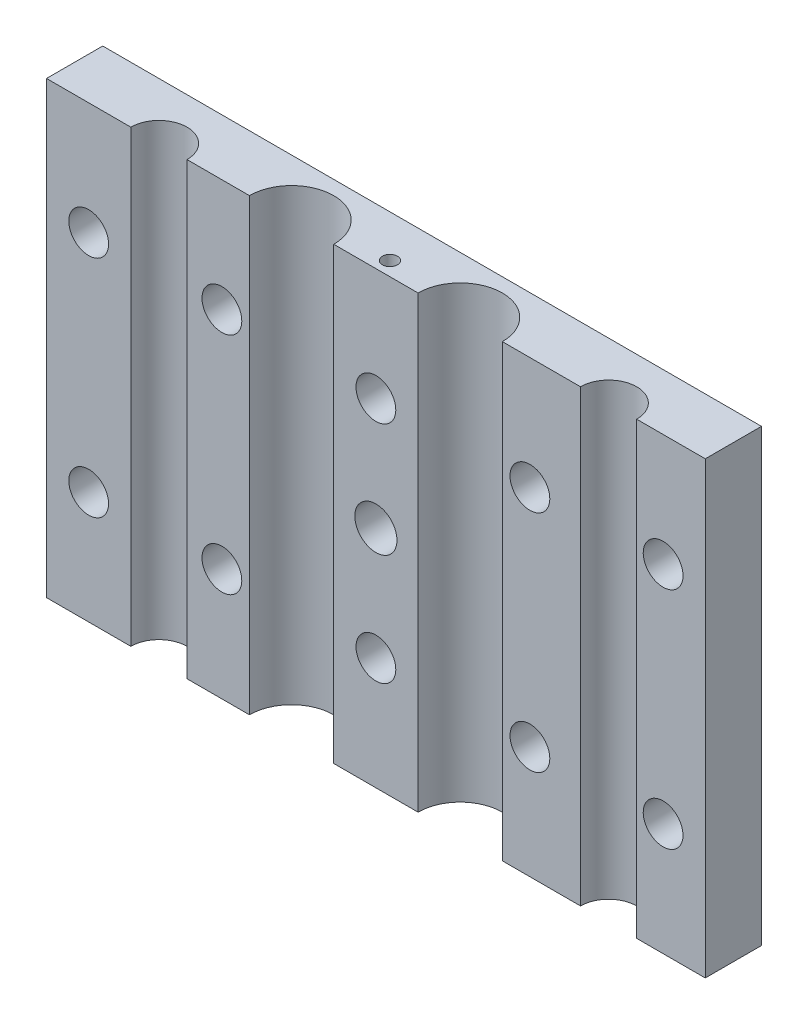
SolidWorks part; units mm, degrees
material "Copper"
ref_plane "Front Plane" through (0, 0, 0) normal (0, 0, 1) x (1, 0, 0)
ref_plane "Top Plane" through (0, 0, 0) normal (0, 1, 0) x (1, 0, 0)
ref_plane "Right Plane" through (0, 0, 0) normal (1, 0, 0) x (0, 0, -1)
sketch "Sketch1" plane through (0, 0, 0) normal (0, 1, 0) x (1, 0, 0)
  line L1 (-37.211, 25.4) -> (37.211, 25.4)
  line L2 (-37.211, 25.4) -> (-37.211, -25.4)
  line L3 (-37.211, -25.4) -> (37.211, -25.4)
  line L4 (37.211, 25.4) -> (37.211, -25.4)
  dimension "D1" = 50.8
  dimension "D2" = 74.422
  dimension "D3" = 37.211
  dimension "D4" = 25.4
extrude "Boss-Extrude1" add sketch "Sketch1" along normal blind 6.35
sketch "Sketch2" plane through (0, 0, 25.4) normal (0, 0, 1) x (1, 0, 0)
  line L0 (-37.211, 0) -> (37.211, 0) construction
  line L1 (-37.211, 6.35) -> (-37.211, 0) construction
  circle A0 centre (-24.511, 0) radius 3.175
  circle A1 centre (26.289, 0) radius 3.175
  dimension "D3" = 6.35
  dimension "D1" = 50.8
  dimension "D2" = 12.7
extrude "Cut-Extrude1" cut sketch "Sketch2" against normal through all
sketch "Sketch3" plane through (0, 0, 25.4) normal (0, 0, 1) x (1, 0, 0)
  line L0 (-21.336, 0) -> (23.114, 0) construction
  circle A0 centre (-9.525, 0) radius 4.7625
  circle A1 centre (9.525, 0) radius 4.7625
  dimension "D1" = 9.525
  dimension "D2" = 19.05
  dimension "D3" = 9.525
extrude "Cut-Extrude2" cut sketch "Sketch3" against normal through all
hole_wizard "#8 Clearance Hole1" positions "Sketch5" profile "Sketch4" hole size "#8" standard "ANSI Inch" end condition through all
sketch "Sketch5" plane through (0, 6.35, 0) normal (0, 1, 0) x (1, 0, 0)
  line L2 (37.211, 25.4) -> (-37.211, 25.4) construction
  line L3 (-37.211, -25.4) -> (37.211, -25.4) construction
  line L4 (-37.211, 25.4) -> (-37.211, -25.4) construction
  line L5 (37.211, -25.4) -> (37.211, 25.4) construction
  point P0 (-32.4485, 12.7)
  point P2 (-32.4485, -12.7)
  point P4 (-17.399, -12.7)
  point P6 (0, -12.7)
  point P8 (17.399, -12.7)
  point P10 (32.4485, -12.7)
  point P12 (32.4485, 12.7)
  point P14 (17.399, 12.7)
  point P16 (0, 12.7)
  point P18 (-17.399, 12.7)
  dimension "D1" = 12.7
  dimension "D2" = 12.7
  dimension "D3" = 4.7625
  dimension "D4" = 4.7625
  dimension "D5" = 19.812
  dimension "D6" = 19.812
sketch "Sketch4" plane through (-32.4485, 6.35, -12.7) normal (1, 0, 0) x (0, 0, 1)
  line L0 (0, 0) -> (0, 6.35)
  line L1 (0, 6.35) -> (2.2479, 6.35)
  line L2 (2.2479, 6.35) -> (2.2479, 0)
  line L5 (2.2479, 0) -> (0, 0)
  line L11 (0, -6.35) -> (0, 107.95) construction
  dimension "Thru Hole Dia." = 4.4958
  dimension "Thru Hole Depth" = 6.35
sketch "Sketch6" plane through (0, 6.35, 0) normal (0, 1, 0) x (1, 0, 0)
  line L0 (-17.399, 17.018) -> (-17.399, 8.382) construction
  line L1 (-13.081, 17.018) -> (-13.081, 8.382)
  line L2 (-21.717, 17.018) -> (-21.717, 8.382)
  line L3 (0, 25.4) -> (0, 0) construction
  line L4 (37.211, 25.4) -> (-37.211, 25.4) construction
  line L5 (37.211, 0) -> (0, 0) construction
  line L6 (37.211, -25.4) -> (37.211, 25.4) construction
  line L7 (17.399, 17.018) -> (17.399, 8.382) construction
  line L8 (13.081, 17.018) -> (13.081, 8.382)
  line L9 (21.717, 17.018) -> (21.717, 8.382)
  line L10 (17.399, -17.018) -> (17.399, -8.382) construction
  line L11 (13.081, -17.018) -> (13.081, -8.382)
  line L12 (21.717, -17.018) -> (21.717, -8.382)
  line L13 (-17.399, -17.018) -> (-17.399, -8.382) construction
  line L14 (-13.081, -17.018) -> (-13.081, -8.382)
  line L15 (-21.717, -17.018) -> (-21.717, -8.382)
  line L16 (0, 17.018) -> (0, 8.382) construction
  line L17 (4.318, 17.018) -> (4.318, 8.382)
  line L18 (-4.318, 17.018) -> (-4.318, 8.382)
  line L19 (0, -17.018) -> (0, -8.382) construction
  line L20 (4.318, -17.018) -> (4.318, -8.382)
  line L21 (-4.318, -17.018) -> (-4.318, -8.382)
  line L22 (-32.4485, 17.018) -> (-32.4485, 8.382) construction
  line L23 (-28.1305, 17.018) -> (-28.1305, 8.382)
  line L24 (-36.7665, 17.018) -> (-36.7665, 8.382)
  line L25 (-32.4485, -17.018) -> (-32.4485, -8.382) construction
  line L26 (-28.1305, -17.018) -> (-28.1305, -8.382)
  line L27 (-36.7665, -17.018) -> (-36.7665, -8.382)
  line L28 (32.4485, 17.018) -> (32.4485, 8.382) construction
  line L29 (28.1305, 17.018) -> (28.1305, 8.382)
  line L30 (36.7665, 17.018) -> (36.7665, 8.382)
  line L31 (32.4485, -17.018) -> (32.4485, -8.382) construction
  line L32 (28.1305, -17.018) -> (28.1305, -8.382)
  line L33 (36.7665, -17.018) -> (36.7665, -8.382)
  arc A0 (-13.081, 17.018) -> (-21.717, 17.018) centre (-17.399, 17.018) ccw
  arc A1 (-21.717, 8.382) -> (-13.081, 8.382) centre (-17.399, 8.382) ccw
  arc A2 (13.081, 17.018) -> (21.717, 17.018) centre (17.399, 17.018) cw
  arc A3 (21.717, 8.382) -> (13.081, 8.382) centre (17.399, 8.382) cw
  arc A4 (13.081, -17.018) -> (21.717, -17.018) centre (17.399, -17.018) ccw
  arc A5 (21.717, -8.382) -> (13.081, -8.382) centre (17.399, -8.382) ccw
  arc A6 (-13.081, -17.018) -> (-21.717, -17.018) centre (-17.399, -17.018) cw
  arc A7 (-21.717, -8.382) -> (-13.081, -8.382) centre (-17.399, -8.382) cw
  arc A11 (4.318, 17.018) -> (-4.318, 17.018) centre (0, 17.018) ccw
  arc A12 (-4.318, 8.382) -> (4.318, 8.382) centre (0, 8.382) ccw
  arc A13 (4.318, -17.018) -> (-4.318, -17.018) centre (0, -17.018) cw
  arc A14 (-4.318, -8.382) -> (4.318, -8.382) centre (0, -8.382) cw
  arc A15 (-28.1305, 17.018) -> (-36.7665, 17.018) centre (-32.4485, 17.018) ccw
  arc A16 (-36.7665, 8.382) -> (-28.1305, 8.382) centre (-32.4485, 8.382) ccw
  arc A17 (-28.1305, -17.018) -> (-36.7665, -17.018) centre (-32.4485, -17.018) cw
  arc A18 (-36.7665, -8.382) -> (-28.1305, -8.382) centre (-32.4485, -8.382) cw
  arc A19 (28.1305, 17.018) -> (36.7665, 17.018) centre (32.4485, 17.018) cw
  arc A20 (36.7665, 8.382) -> (28.1305, 8.382) centre (32.4485, 8.382) cw
  arc A21 (28.1305, -17.018) -> (36.7665, -17.018) centre (32.4485, -17.018) ccw
  arc A22 (36.7665, -8.382) -> (28.1305, -8.382) centre (32.4485, -8.382) ccw
  point P3 (-17.399, 12.7)
  point P18 (17.399, 12.7)
  point P25 (17.399, -12.7)
  point P32 (-17.399, -12.7)
  point P39 (0, 12.7)
  point P46 (0, -12.7)
  point P54 (-32.4485, 12.7)
  point P61 (-32.4485, -12.7)
  point P68 (32.4485, 12.7)
  point P75 (32.4485, -12.7)
  dimension "D1" = 8.636
  dimension "D2" = 12.7
  dimension "D3" = 8.636
  dimension "D4" = 12.7
  dimension "D5" = 8.636
  dimension "D6" = 8.636
  dimension "D7" = 12.7
  dimension "D8" = 8.636
  dimension "D9" = 8.636
extrude "Cut-Extrude3" cut sketch "Sketch6" against normal blind 3.175
sketch "Sketch7" plane through (0, 6.35, 0) normal (0, 1, 0) x (1, 0, 0)
  circle A0 centre (0, 0) radius 2.3813
  dimension "D1" = 4.7625
extrude "Cut-Extrude4" cut sketch "Sketch7" against normal through all
sketch "Sketch8" plane through (0, 0, 25.4) normal (0, 0, 1) x (1, 0, 0)
  line L0 (-4.7625, 0) -> (4.7625, 0) construction
  circle A0 centre (0, 1.5875) radius 0.8509
  dimension "D2" = 1.7018
  dimension "D1" = 1.5875
extrude "Cut-Extrude5" cut sketch "Sketch8" against normal blind 9.525
move or copy body "Body-Move/Copy1" bodies to move or copy 112 copy no rotation origin (0, 3.175, 0) rotation axis (-1, 0, 0) rotation angle 90
